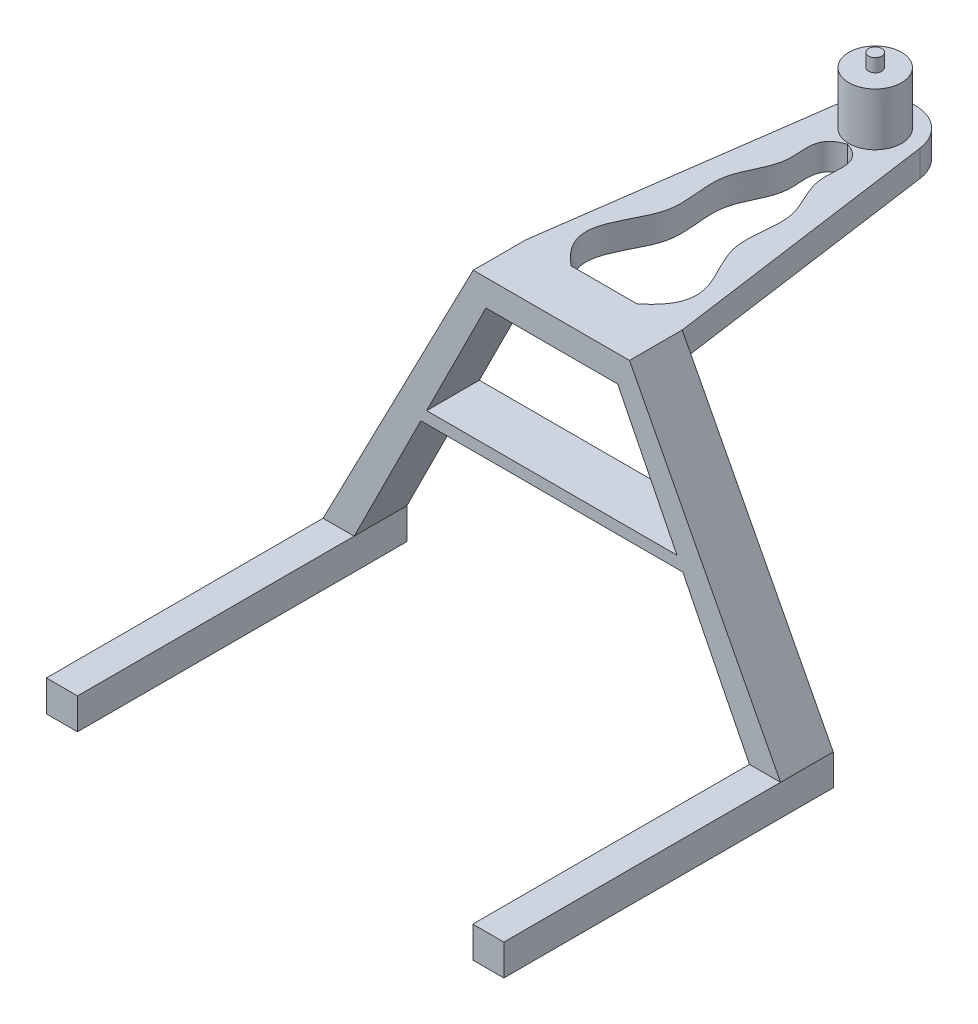
SolidWorks part; units mm, degrees
ref_plane "Front Plane" through (0, 0, 0) normal (0, 0, 1) x (1, 0, 0)
ref_plane "Top Plane" through (0, 0, 0) normal (0, 1, 0) x (1, 0, 0)
ref_plane "Right Plane" through (0, 0, 0) normal (1, 0, 0) x (0, 0, -1)
sketch "Sketch1" plane through (0, 0, 0) normal (0, 0, 1) x (1, 0, 0)
  line L0 (821.9694, 0) -> (762, 0)
  line L1 (0, 0) -> (-59.9694, 0)
  line L2 (0, 0) -> (0, 59.9694)
  line L3 (0, 59.9694) -> (-59.9694, 59.9694)
  line L4 (-59.9694, 0) -> (-59.9694, 59.9694)
  line L5 (821.9694, 0) -> (821.9694, 59.9694)
  line L6 (821.9694, 59.9694) -> (762, 59.9694)
  line L7 (762, 0) -> (762, 59.9694)
  dimension "D1" = 59.9694
  dimension "D2" = 59.9694
  dimension "D3" = 59.9694
  dimension "D4" = 59.9694
  dimension "D5" = 0
  dimension "D6" = 762
extrude "Boss-Extrude1" add sketch "Sketch1" along normal blind 635
sketch "Sketch5" plane through (0, 0, 0) normal (0, 0, 1) x (1, 0, 0)
  line L0 (254, 567.9694) -> (508, 567.9694)
  line L1 (0, 59.9694) -> (-59.9694, 59.9694) construction
  line L2 (0, 0) -> (0, 59.9694) construction
  line L4 (229.5169, 618.7694) -> (530.7401, 618.7694)
  line L6 (-59.9694, 59.9694) -> (229.5169, 618.7694)
  line L7 (0, 59.9694) -> (254, 567.9694)
  line L8 (508, 567.9694) -> (762, 59.9694)
  line L9 (762, 59.9694) -> (821.9694, 59.9694)
  line L10 (821.9694, 59.9694) -> (530.7401, 618.7694)
  line L11 (0, 59.9694) -> (-59.9694, 59.9694)
  point P4 (-29.9847, 59.9694)
  point P15 (203.2, 567.9694)
  point P18 (254, 567.9694)
  point P19 (558.8, 564.929)
  point P20 (508, 567.9694)
  dimension "D1" = 254
  dimension "D2" = 508
  dimension "D3" = 254
  dimension "D5" = 50.8
  dimension "D6" = 50.8
  dimension "D7" = 50.8
extrude "Boss-Extrude2" add sketch "Sketch5" along normal blind 101.6
sketch "Sketch6" plane through (0, 0, 0) normal (0, 0, 1) x (1, 0, 0)
  line L0 (84.7738, 339.3694) -> (676.3547, 339.3694)
  line L1 (229.5169, 618.7694) -> (-59.9694, 59.9694) construction
  line L2 (821.9694, 59.9694) -> (530.7401, 618.7694) construction
  line L3 (676.3547, 339.3694) -> (688.0938, 316.8449)
  line L4 (688.0938, 316.8449) -> (73.1049, 316.8449)
  line L5 (73.1049, 316.8449) -> (84.7738, 339.3694)
  dimension "D1" = 25.4
extrude "Boss-Extrude3" add sketch "Sketch6" along normal blind 101.6
sketch "Sketch7" plane through (0, 618.7694, 0) normal (0, 1, 0) x (1, 0, 0)
  line L6 (229.5169, 0) -> (303.9285, 533.3252)
  line L7 (530.7401, 0) -> (456.3285, 533.3252)
  line L8 (229.5169, 0) -> (530.7401, 0)
  arc A1 (303.9285, 533.3252) -> (456.3285, 533.3252) centre (380.1285, 522.6935) cw
extrude "Boss-Extrude4" add sketch "Sketch7" against normal blind 50.8
sketch "Sketch9" plane through (0, 618.7694, 0) normal (0, 1, 0) x (1, 0, 0)
  line L0 (316.6389, 0) -> (443.6389, 0)
  line L2 (229.5169, -101.6) -> (229.5169, 0) construction
  spline S0 degree 3 poles (316.6389, 0) (226.1849, 73.2726) (347.4024, 153.8101) (298.129, 296.0762) (366.7784, 382.1462) (332.7883, 454.1416) (380.1389, 469.3957) knots 0 0 0 0 0.403522 0.617987 0.803164 1 1 1 1
  spline S1 degree 3 poles (443.6389, 0) (534.093, 73.2726) (412.8755, 153.8101) (462.1489, 296.0762) (393.4994, 382.1462) (427.4895, 454.1416) (380.1389, 469.3957) knots 0 0 0 0 0.403522 0.617987 0.803164 1 1 1 1
  dimension "D1" = 127
  dimension "D2" = 87.122
  dimension "D3" = 30.48
  dimension "D4" = 30.48
  dimension "D5" = 30.48
  dimension "D6" = 30.48
  dimension "D7" = 30.48
  dimension "D8" = 30.48
extrude "Cut-Extrude1" cut sketch "Sketch9" against normal through all
sketch "Sketch10" plane through (0, 618.7694, 0) normal (0, 1, 0) x (1, 0, 0)
  circle A0 centre (380.1285, 522.6935) radius 50.8
  dimension "D1" = 101.6
extrude "Boss-Extrude5" add sketch "Sketch10" along normal blind 101.6
sketch "Sketch11" plane through (0, 720.3694, 0) normal (0, 1, 0) x (1, 0, 0)
  circle A0 centre (380.1285, 522.6935) radius 12.7
  dimension "D1" = 25.4
extrude "Boss-Extrude6" add sketch "Sketch11" along normal blind 25.4
